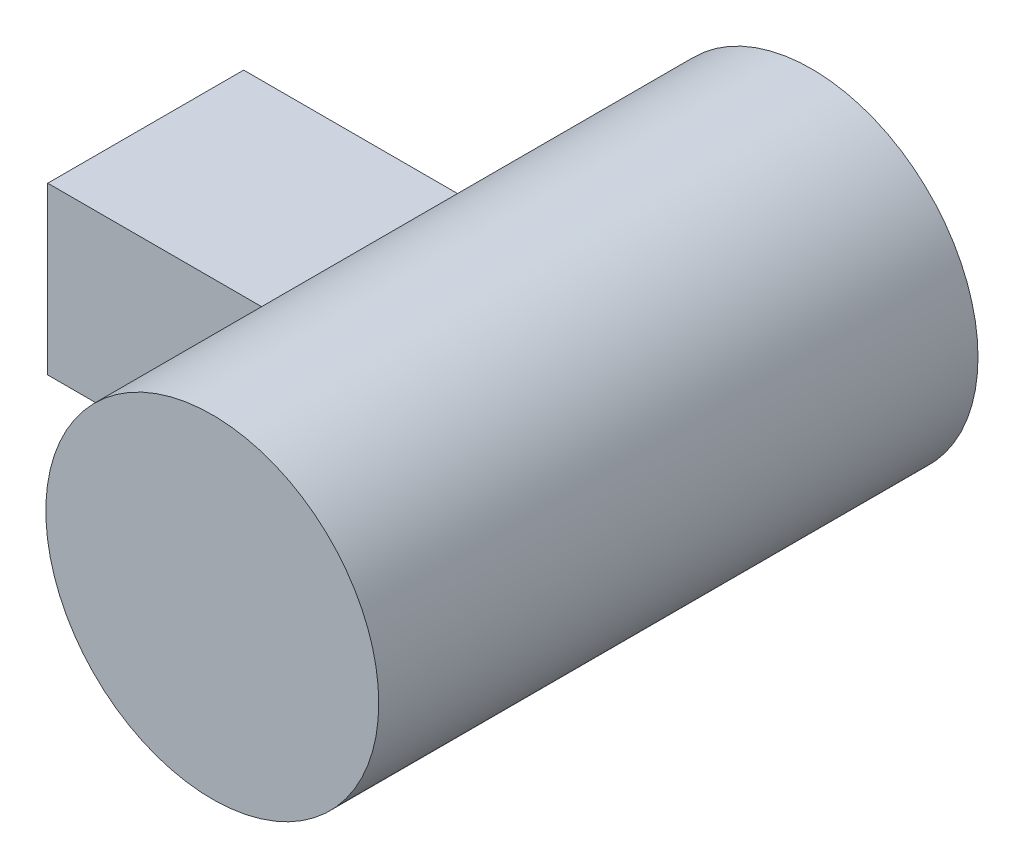
SolidWorks part; units mm, degrees
ref_plane "Front Plane" through (0, 0, 0) normal (0, 0, 1) x (1, 0, 0)
ref_plane "Top Plane" through (0, 0, 0) normal (0, 1, 0) x (1, 0, 0)
ref_plane "Right Plane" through (0, 0, 0) normal (1, 0, 0) x (0, 0, -1)
sketch "Sketch1" plane through (0, 0, 0) normal (0, 0, 1) x (1, 0, 0)
  circle A0 centre (0, 0) radius 31.75
  dimension "D1" = 63.5
extrude "Boss-Extrude1" add sketch "Sketch1" along normal mid plane 114.3 contours A0
sketch "Sketch2" plane through (0, 0, 0) normal (1, 0, 0) x (0, 0, -1)
  line L1 (18.6845, -15.8412) -> (-18.6845, -15.8412)
  line L2 (18.6845, -15.8412) -> (18.6845, 15.8412)
  line L3 (18.6845, 15.8412) -> (-18.6845, 15.8412)
  line L4 (-18.6845, -15.8412) -> (-18.6845, 15.8412)
  line L5 (18.6845, -15.8412) -> (-18.6845, 15.8412) construction
  line L6 (18.6845, 15.8412) -> (-18.6845, -15.8412) construction
  point P0 (0, 0)
extrude "Boss-Extrude2" add sketch "Sketch2" against normal blind 69.85
